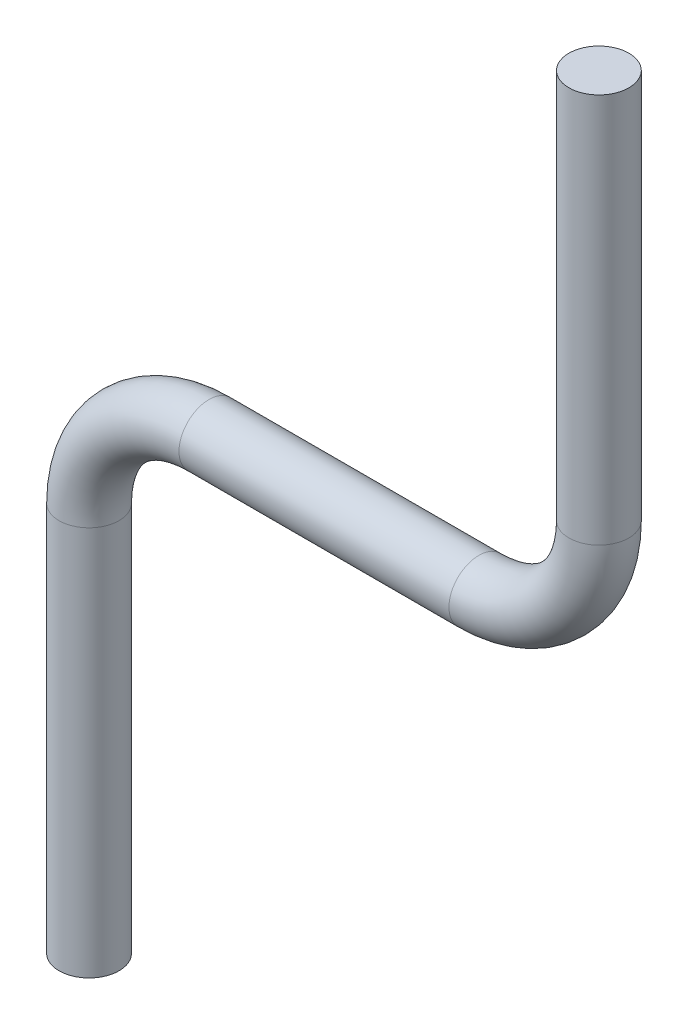
SolidWorks part; units mm, degrees
ref_plane "正面" through (0, 0, 0) normal (0, 0, 1) x (1, 0, 0)
ref_plane "平面" through (0, 0, 0) normal (0, 1, 0) x (1, 0, 0)
ref_plane "右側面" through (0, 0, 0) normal (1, 0, 0) x (0, 0, -1)
sketch "ｽｹｯﾁ18" plane through (0, 0, 0) normal (0, 1, 0) x (1, 0, 0)
  circle A0 centre (0, 0) radius 2
sketch "ｽｹｯﾁ19" plane through (0, 0, 0) normal (0, 0, 1) x (1, 0, 0)
  line L0 (0, 0) -> (0, 26)
  line L1 (8, 34) -> (26, 34)
  line L2 (34, 42) -> (34, 68)
  arc A0 (8, 34) -> (0, 26) centre (8, 26) ccw
  arc A1 (34, 42) -> (26, 34) centre (26, 42) cw
  point P7 (0, 34)
  point P10 (34, 34)
  dimension "D4" = 8
  dimension "D5" = 8
  dimension "D1" = 34
  dimension "D2" = 34
  dimension "D3" = 34
sweep "ｽｲｰﾌﾟ6" add profiles "ｽｹｯﾁ18" path "ｽｹｯﾁ19"
